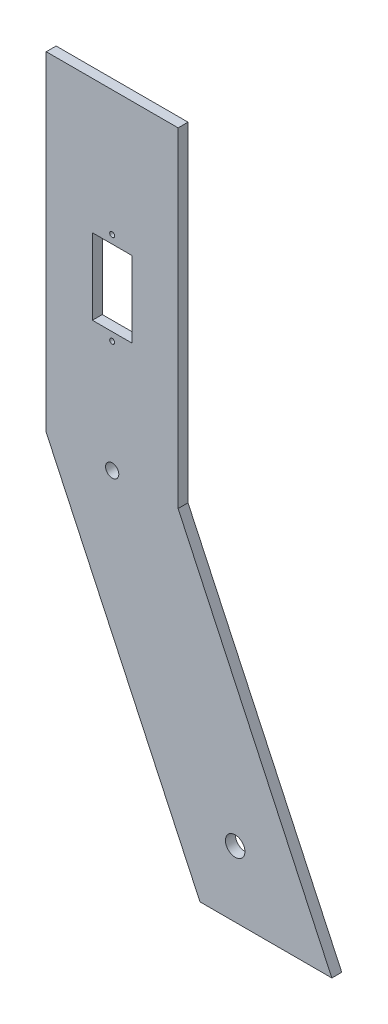
SolidWorks part; units mm, degrees
ref_plane "Front Plane" through (0, 0, 0) normal (0, 0, 1) x (1, 0, 0)
ref_plane "Top Plane" through (0, 0, 0) normal (0, 1, 0) x (1, 0, 0)
ref_plane "Right Plane" through (0, 0, 0) normal (1, 0, 0) x (0, 0, -1)
sketch "Croquis1" plane through (0, 0, 0) normal (0, 0, 1) x (1, 0, 0)
  line L0 (0, 0) -> (-40, 0)
  line L1 (-86.6308, 100) -> (-46.6308, 100) construction
  line L2 (-86.6308, 100) -> (-40, 0)
  line L3 (-46.6308, 100) -> (0, 0)
  line L4 (-86.6308, 100) -> (-86.6308, 200)
  line L5 (-86.6308, 200) -> (-46.6308, 200)
  line L6 (-46.6308, 200) -> (-46.6308, 100)
  line L7 (-29.3262, 20) -> (-20, 0) construction
  line L8 (-66.6308, 180) -> (-66.6308, 200) construction
  line L9 (-66.6308, 180) -> (-66.6308, 100) construction
  line L10 (-60.6308, 159.4581) -> (-72.6308, 159.4581)
  line L11 (-72.6308, 159.4581) -> (-72.6308, 136.4581)
  line L12 (-72.6308, 136.4581) -> (-60.6308, 136.4581)
  line L13 (-60.6308, 159.4581) -> (-60.6308, 136.4581)
  circle A0 centre (-29.3262, 20) radius 2.95
  circle A2 centre (-66.6308, 152.9581) radius 1.25 construction
  circle A3 centre (-66.6308, 133.9581) radius 0.75
  circle A4 centre (-66.6308, 161.9581) radius 0.75
  circle A5 centre (-66.6308, 100) radius 2
  point P19 (-66.6308, 136.4581)
  point P20 (-66.6308, 159.4581)
  dimension "D6" = 5.9
  dimension "D8" = 1.5
  dimension "D11" = 2.5
  dimension "D7" = 1.5
  dimension "D14" = 2.5
  dimension "D16" = 4
  dimension "D1" = 100
  dimension "D2" = 40
  dimension "D3" = 65
  dimension "D4" = 100
  dimension "D5" = 20
  dimension "D9" = 23
  dimension "D10" = 12
  dimension "D12" = 16.5
  dimension "D13" = 47.0419
  dimension "D15" = 2.5
extrude "Saliente-Extruir1" add sketch "Croquis1" along normal blind 3
